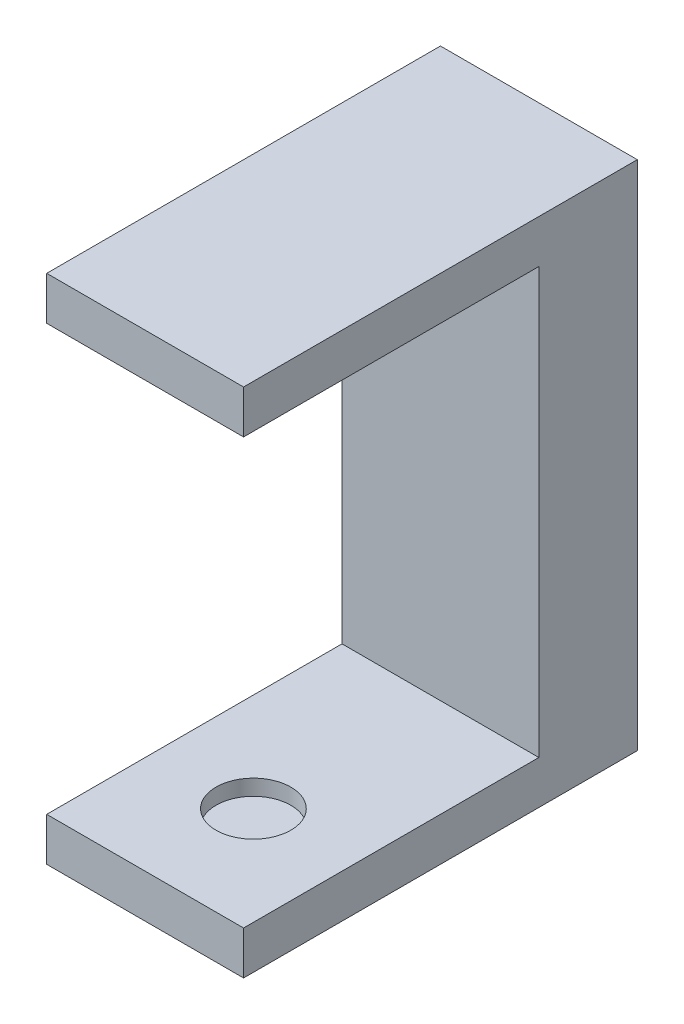
SolidWorks part; units mm, degrees
ref_plane "Front Plane" through (0, 0, 0) normal (1, 0, 0) x (0, 1, 0)
ref_plane "Top Plane" through (0, 0, 0) normal (0, 0, 1) x (0, 1, 0)
ref_plane "Right Plane" through (0, 0, 0) normal (0, 1, 0) x (-1, 0, 0)
sketch "Sketch1" plane through (0, 0, 0) normal (0, 0, 1) x (0, 1, 0)
  line L1 (-13, -5) -> (13, -5)
  line L2 (-13, -5) -> (-13, 5)
  line L3 (-13, 5) -> (13, 5)
  line L4 (13, -5) -> (13, 5)
  line L5 (-13, -5) -> (13, 5) construction
  line L6 (-13, 5) -> (13, -5) construction
  point P0 (0, 0)
extrude "Boss-Extrude1" add sketch "Sketch1" along normal blind 20 contours L1 L4 L3 L2
sketch "Sketch2" plane through (0, 0, 20) normal (0, 0, 1) x (1, 0, 0)
  line L0 (5, -13) -> (5, 13) construction
  line L1 (-5, 13) -> (5, 13) construction
  line L2 (-5, 13) -> (-5, 10.8) construction
  line L3 (-5, 10.8) -> (5, 10.8) construction
  line L4 (5, 13) -> (5, 10.8) construction
  line L6 (-5, -13) -> (5, -13) construction
  line L7 (-5, -13) -> (-5, -10.8) construction
  line L8 (-5, -10.8) -> (5, -10.8) construction
  line L9 (5, -13) -> (5, -10.8) construction
  line L10 (-5, 10.8) -> (5, 10.8)
  line L11 (-5, 10.8) -> (-5, -10.8)
  line L12 (-5, -10.8) -> (5, -10.8)
  line L13 (5, 10.8) -> (5, -10.8)
extrude "Cut-Extrude1" cut sketch "Sketch2" against normal blind 15
sketch "Sketch3" plane through (0, -10.8, 0) normal (0, 1, 0) x (-1, 0, 0)
  line L1 (-5, 20) -> (0, 20) construction
  line L2 (-5, 20) -> (-5, 14.5) construction
  line L3 (-5, 14.5) -> (0, 14.5) construction
  line L4 (0, 20) -> (0, 14.5) construction
  circle A0 centre (0, 14.5) radius 1.9
extrude "Cut-Extrude2" cut sketch "Sketch3" against normal blind 0.8 contours A0
mirror "Mirror1" about plane through (0, 0, 0) normal (0, 1, 0) of "Cut-Extrude2"
